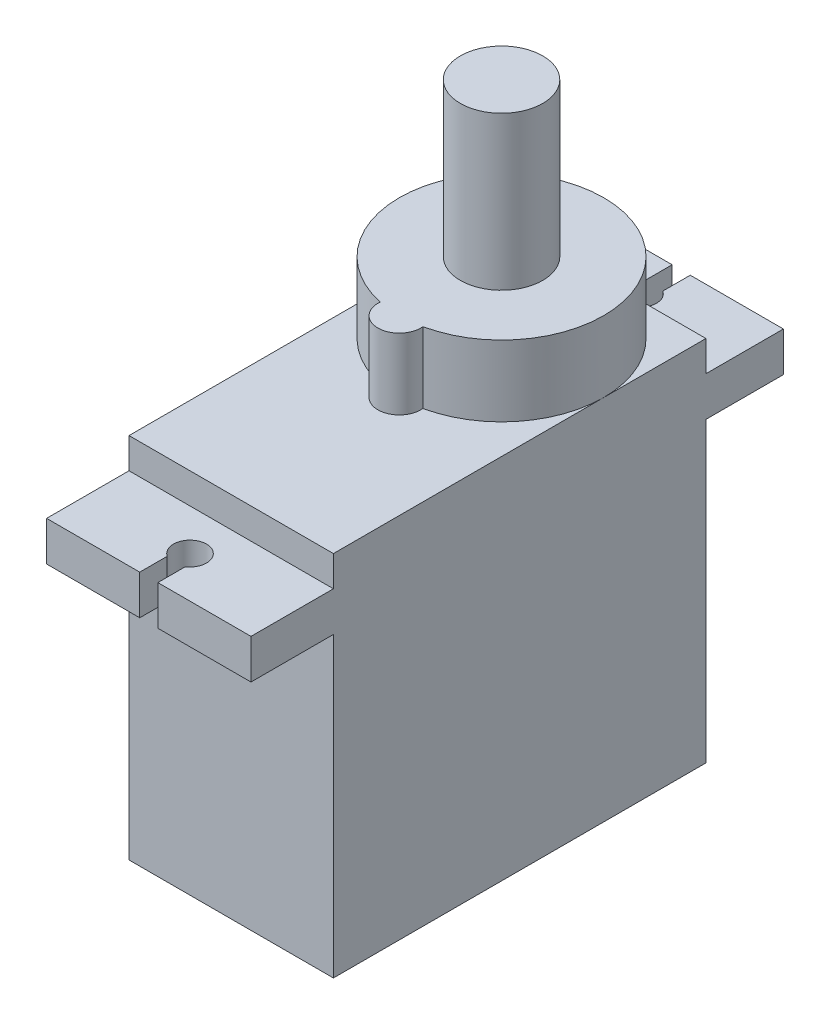
SolidWorks part; units mm, degrees
ref_plane "前视基准面" through (0, 0, 0) normal (0, 0, 1) x (1, 0, 0)
ref_plane "上视基准面" through (0, 0, 0) normal (0, 1, 0) x (1, 0, 0)
ref_plane "右视基准面" through (0, 0, 0) normal (1, 0, 0) x (0, 0, -1)
sketch "草图1" plane through (0, 0, 0) normal (0, 0, 1) x (1, 0, 0)
  line L1 (-6.2, -11.15) -> (6.2, -11.15)
  line L2 (-6.2, -11.15) -> (-6.2, 11.15)
  line L3 (-6.2, 11.15) -> (6.2, 11.15)
  line L4 (6.2, -11.15) -> (6.2, 11.15)
  line L5 (-6.2, -11.15) -> (6.2, 11.15) construction
  line L6 (-6.2, 11.15) -> (6.2, -11.15) construction
  point P0 (0, 0)
  dimension "D1" = 12.4
  dimension "D2" = 22.3
extrude "凸台-拉伸1" add sketch "草图1" along normal blind 22.6
sketch "草图2" plane through (0, 11.15, 0) normal (0, 1, 0) x (1, 0, 0)
  arc A0 (1.2928, -12.2637) -> (-1.2928, -12.2637) centre (0, -6.2) ccw
  arc A1 (-1.2928, -12.2637) -> (1.2928, -12.2637) centre (0, -12.4) ccw
  dimension "D2" = 2.6
  dimension "D1" = 6.2
extrude "凸台-拉伸2" add sketch "草图2" along normal blind 4.3
sketch "草图3" plane through (0, 15.45, 0) normal (0, 1, 0) x (1, 0, 0)
  circle A0 centre (0, -6.2) radius 2.5
  dimension "D1" = 5
extrude "凸台-拉伸3" add sketch "草图3" along normal blind 9.3
ref_plane "基准面1" through (0, 9.3, 0) normal (0, 1, 0) x (1, 0, 0)
sketch "草图4" plane through (0, 9.3, 0) normal (0, 1, 0) x (1, 0, 0)
  line L0 (6.2, -22.6) -> (-6.2, -22.6) construction
  line L1 (6.2, -22.6) -> (-6.2, -22.6)
  line L2 (6.2, -22.6) -> (6.2, -27.6)
  line L3 (6.2, -27.6) -> (0.55, -27.6)
  line L4 (-6.2, -27.6) -> (-6.2, -22.6)
  line L5 (0, -24.5947) -> (0, -20.3237) construction
  line L6 (7.4208, -25.1) -> (1, -25.1) construction
  line L7 (0.55, -25.1) -> (-7.5825, -25.1) construction
  line L8 (-0.55, -27.6) -> (-6.2, -27.6)
  line L9 (-0.55, -25.9352) -> (-0.55, -27.6)
  line L10 (0.55, -25.9352) -> (0.55, -27.6)
  line L11 (-10.9405, -11.45) -> (9.6954, -11.45) construction
  line L12 (0.55, 2.2) -> (-7.5825, 2.2) construction
  line L13 (7.4208, 2.2) -> (1, 2.2) construction
  line L14 (0.55, 3.0352) -> (0.55, 4.7)
  line L15 (-0.55, 3.0352) -> (-0.55, 4.7)
  line L16 (-0.55, 4.7) -> (-6.2, 4.7)
  line L17 (-6.2, 4.7) -> (-6.2, -0.3)
  line L18 (6.2, 4.7) -> (0.55, 4.7)
  line L19 (6.2, -0.3) -> (6.2, 4.7)
  line L20 (6.2, -0.3) -> (-6.2, -0.3)
  arc A1 (0.55, -25.9352) -> (-0.55, -25.9352) centre (0, -25.1) ccw
  arc A2 (0.55, 3.0352) -> (-0.55, 3.0352) centre (0, 2.2) cw
  dimension "D2" = 2
  dimension "D1" = 5
  dimension "D3" = 2.5
  dimension "D4" = 11.15
extrude "凸台-拉伸4" add sketch "草图4" against normal blind 2.4
sketch "草图5" plane through (0, 0, 0) normal (0, 0, -1) x (-1, 0, 0)
  line L0 (-9.0909, -6.65) -> (10.0493, -6.65) construction
  line L1 (6.2, -11.15) -> (-6.2, -11.15) construction
  line L2 (0, -12.3081) -> (0, -1.4265) construction
  circle A0 centre (0, -6.65) radius 0.6
  circle A1 centre (-1.21, -6.65) radius 0.6
  circle A2 centre (1.21, -6.65) radius 0.6
  dimension "D2" = 1.2
  dimension "D1" = 4.5
  dimension "D3" = 1.21
  dimension "D4" = 1.21
extrude "凸台-拉伸5" add sketch "草图5" along normal blind 2.3
